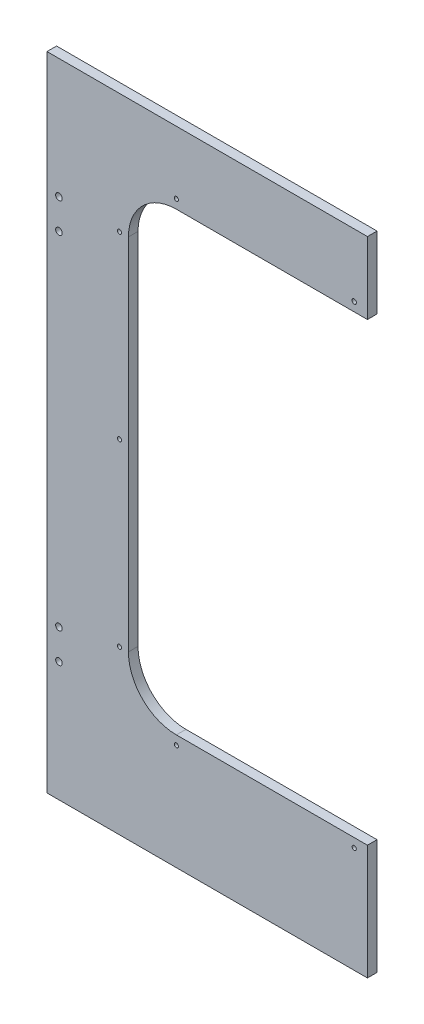
SolidWorks part; units mm, degrees
ref_plane "Front Plane" through (0, 0, 0) normal (0, 0, 1) x (1, 0, 0)
ref_plane "Top Plane" through (0, 0, 0) normal (0, 1, 0) x (1, 0, 0)
ref_plane "Right Plane" through (0, 0, 0) normal (1, 0, 0) x (0, 0, -1)
sketch "Sketch1" plane through (0, 0, 0) normal (0, 0, 1) x (1, 0, 0)
  line L0 (0, -1000) -> (0, 49000) construction
  line L1 (-267.5, 268) -> (0, 268)
  line L2 (-267.5, 268) -> (-267.5, -268)
  line L3 (-267.5, -268) -> (0, -268)
  line L4 (0, -268) -> (0, 268)
  line L5 (-267.5, 268) -> (0, 0) construction
  line L6 (-267.5, -268) -> (0, 0) construction
  line L7 (-257.5093, 257.9907) -> (0, 257.9907) construction
  line L8 (-257.5093, 257.9907) -> (-257.5093, -257.9907) construction
  line L9 (-257.5093, -257.9907) -> (0, -257.9907) construction
  line L11 (-1000, 0) -> (49000, 0) construction
  circle A0 centre (-257.5093, -143) radius 2.75
  circle A3 centre (-257.5, 168) radius 2.75
  circle A6 centre (-257.5093, 143) radius 2.75
  circle A10 centre (-257.5, -168) radius 2.75
  dimension "D3" = 5.5
  dimension "D1" = 267.5
  dimension "D2" = 100
  dimension "D4" = 25
  dimension "D5" = 536
extrude "Boss-Extrude1" add sketch "Sketch1" along normal blind 8
sketch "Sketch2" plane through (0, 0, 8) normal (0, 0, 1) x (1, 0, 0)
  line L0 (-267.5, 268) -> (-267.5, -268) construction
  line L2 (0, 268) -> (-267.5, 268) construction
  line L17 (-159.5, 208) -> (160.5, 208)
  line L18 (-199.5, 168) -> (-199.5, -132)
  line L19 (-159.5, -172) -> (160.5, -172)
  line L20 (200.5, 168) -> (200.5, -132)
  arc A0 (-199.5, -132) -> (-159.5, -172) centre (-159.5, -132) ccw
  arc A1 (160.5, -172) -> (200.5, -132) centre (160.5, -132) ccw
  arc A2 (160.5, 208) -> (200.5, 168) centre (160.5, 168) cw
  arc A3 (-159.5, 208) -> (-199.5, 168) centre (-159.5, 168) ccw
  point P0 (0, 0)
  point P7 (-199.5, -172)
  point P17 (200.5, 208)
  point P20 (-199.5, 208)
  dimension "D4" = 40
  dimension "D1" = 400
  dimension "D2" = 380
  dimension "D3" = 68
  dimension "D5" = 60
extrude "Cut-Extrude1" cut sketch "Sketch2" against normal blind 8
sketch "Sketch3" plane through (0, 0, 8) normal (0, 0, 1) x (1, 0, 0)
  circle A0 centre (-11.0588, 215.5) radius 1.8643
  circle A1 centre (-159.5, 215.5) radius 1.75
  circle A2 centre (-207, 168) radius 1.75
  circle A3 centre (-207, 18) radius 1.75
  circle A4 centre (-207, -132) radius 1.75
  circle A5 centre (-159.5, -179.5) radius 1.75
  circle A6 centre (-11.0588, -179.5) radius 1.75
extrude "Cut-Extrude2" cut sketch "Sketch3" against normal blind 10
